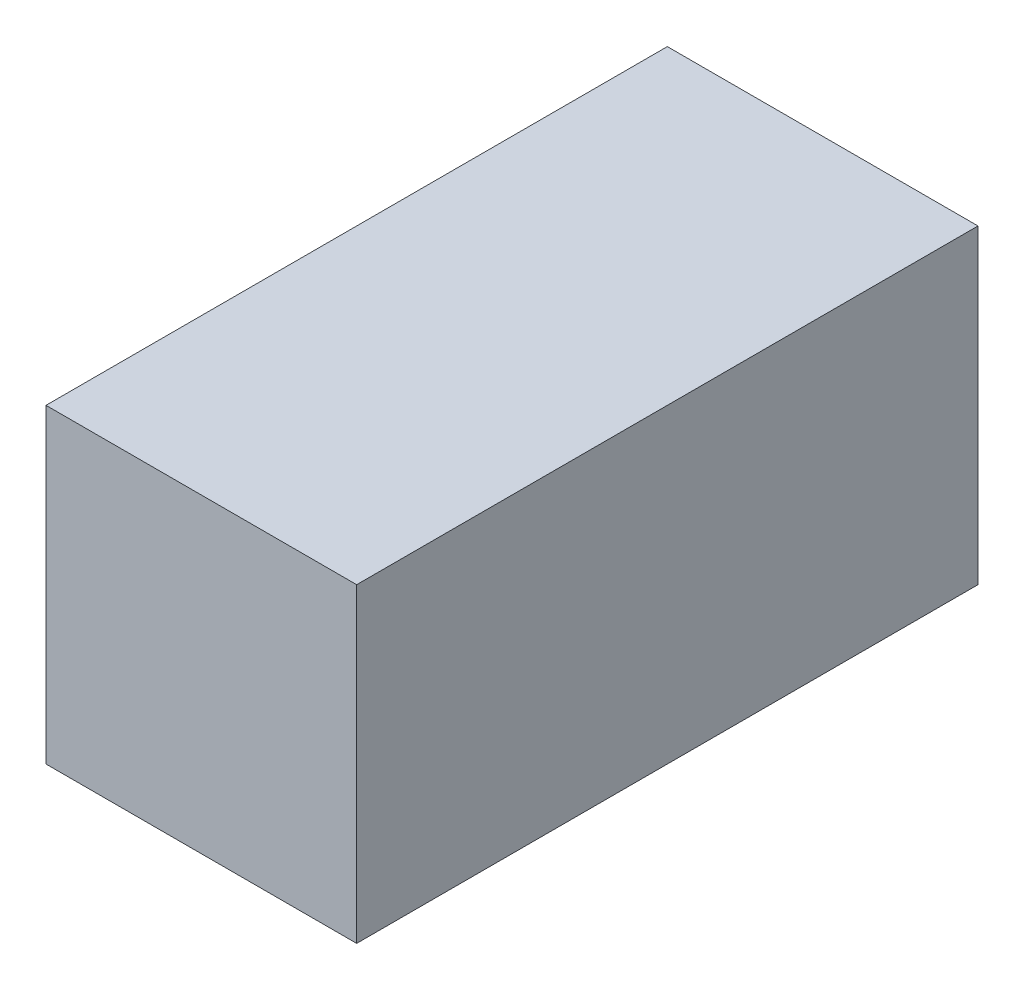
SolidWorks part; units mm, degrees
ref_plane "Alzado" through (0, 0, 0) normal (0, 0, 1) x (1, 0, 0)
ref_plane "Planta" through (0, 0, 0) normal (0, 1, 0) x (1, 0, 0)
ref_plane "Vista lateral" through (0, 0, 0) normal (1, 0, 0) x (0, 0, -1)
sketch "Croquis1" plane through (0, 0, 0) normal (0, 0, 1) x (1, 0, 0)
  line L1 (-18.566, 18.5853) -> (6.434, 18.5853)
  line L2 (-18.566, 18.5853) -> (-18.566, -6.4147)
  line L3 (-18.566, -6.4147) -> (6.434, -6.4147)
  line L4 (6.434, 18.5853) -> (6.434, -6.4147)
  line L5 (-18.566, 18.5853) -> (6.434, -6.4147) construction
  line L6 (-18.566, -6.4147) -> (6.434, 18.5853) construction
  point P0 (-6.066, 6.0853)
extrude "Saliente-Extruir1" add sketch "Croquis1" against normal blind 50
